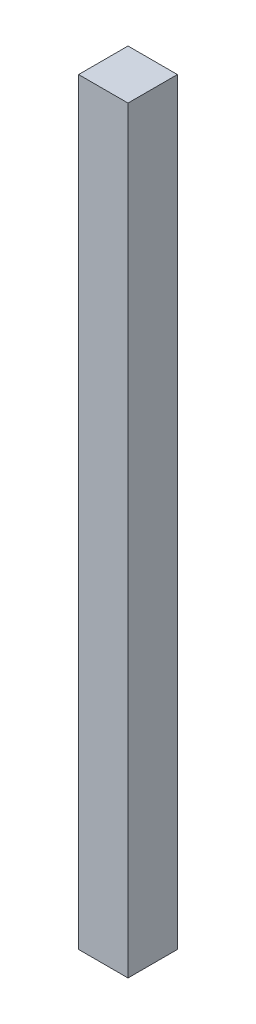
SolidWorks part; units mm, degrees
ref_plane "前视基准面" through (0, 0, 0) normal (0, 0, 1) x (1, 0, 0)
ref_plane "上视基准面" through (0, 0, 0) normal (0, 1, 0) x (1, 0, 0)
ref_plane "右视基准面" through (0, 0, 0) normal (1, 0, 0) x (0, 0, -1)
sketch "草图1" plane through (0, 0, 0) normal (0, 1, 0) x (1, 0, 0)
  line L1 (-7.5, 7.5) -> (7.5, 7.5)
  line L2 (-7.5, 7.5) -> (-7.5, -7.5)
  line L3 (-7.5, -7.5) -> (7.5, -7.5)
  line L4 (7.5, 7.5) -> (7.5, -7.5)
  line L5 (-7.5, 7.5) -> (7.5, -7.5) construction
  line L6 (-7.5, -7.5) -> (7.5, 7.5) construction
  point P0 (0, 0)
  dimension "D1" = 15
  dimension "D2" = 15
extrude "凸台-拉伸1" add sketch "草图1" along normal blind 230
